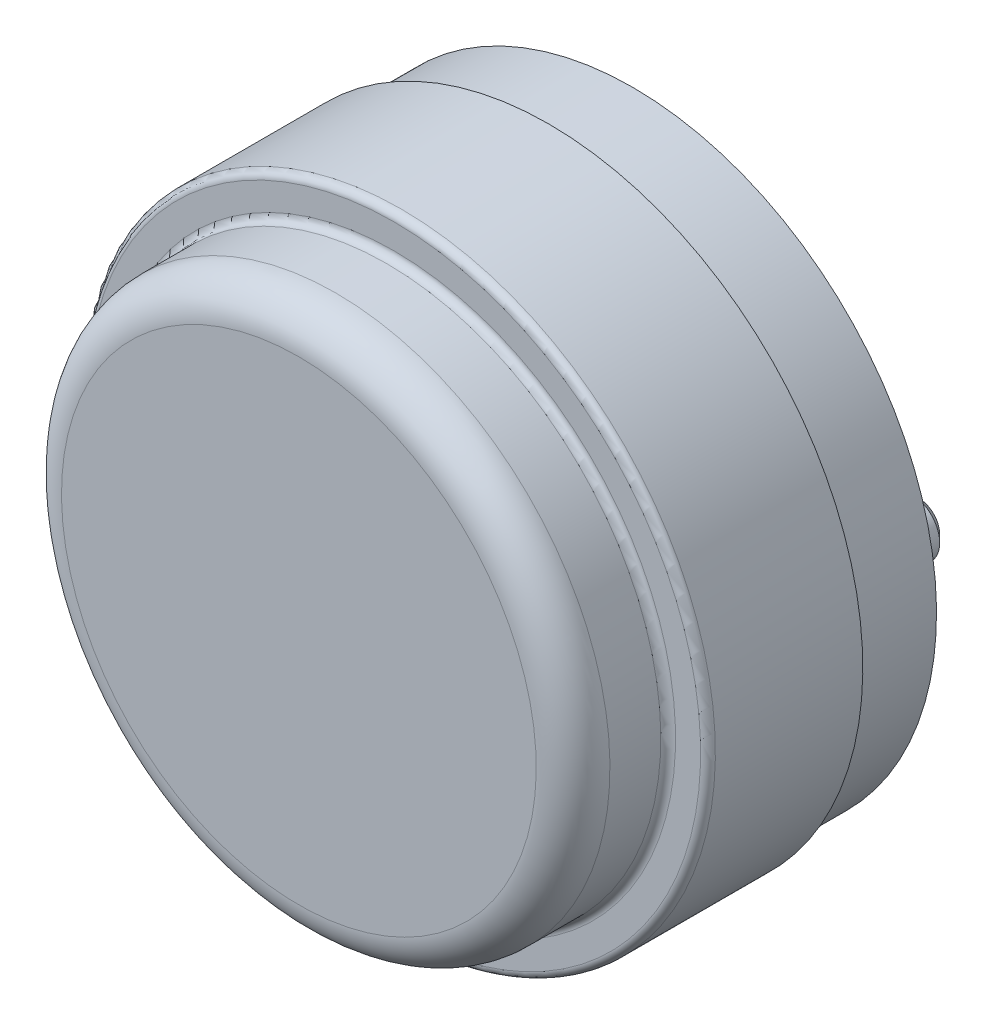
SolidWorks part; units mm, degrees
material "PP Copolymer"
ref_plane "Front" through (0, 0, 0) normal (0, 0, 1) x (1, 0, 0)
ref_plane "Top" through (0, 0, 0) normal (0, 1, 0) x (1, 0, 0)
ref_plane "Right" through (0, 0, 0) normal (1, 0, 0) x (0, 0, -1)
sketch "Sketch2" plane through (0, 0, 0) normal (1, 0, 0) x (0, 0, -1)
  line L0 (0, 0) -> (-7.62, 0) construction
  line L1 (-7.62, 0) -> (-11.5062, 0) construction
  line L2 (-7.62, 0) -> (-11.5062, 0)
  line L33 (-11.5062, 8.1788) -> (-11.5062, 0)
  line L34 (-8.4836, 9.4488) -> (-10.2362, 9.4488)
  line L35 (-8.2296, 10.5664) -> (-8.2296, 9.7028)
  line L36 (-2.8956, 10.8204) -> (-7.9756, 10.8204)
  line L37 (-2.8956, 10.4648) -> (-2.8956, 10.8204)
  line L38 (0, 10.4648) -> (-2.8956, 10.4648)
  line L39 (0, 5.08) -> (0, 10.4648)
  line L40 (-7.62, 5.08) -> (0, 5.08)
  line L41 (-7.62, 0) -> (-7.62, 5.08)
  arc A13 (-10.2362, 9.4488) -> (-11.5062, 8.1788) centre (-10.2362, 8.1788) ccw
  arc A14 (-8.4836, 9.4488) -> (-8.2296, 9.7028) centre (-8.4836, 9.7028) ccw
  arc A15 (-7.9756, 10.8204) -> (-8.2296, 10.5664) centre (-7.9756, 10.5664) ccw
  dimension "D4" = 1.27
  dimension "D5" = 0.254
  dimension "D7" = 0.254
  dimension "D1" = 7.62
  dimension "D2" = 8.1788
  dimension "D3" = 3.8862
  dimension "D6" = 3.2766
  dimension "D8" = 1.3716
  dimension "D9" = 5.08
  dimension "D10" = 0.3556
  dimension "D11" = 5.3848
  dimension "D12" = 2.8956
revolve "Revolve1" add sketch "Sketch2" angle 360 about L0
sketch "Sketch3" plane through (0, 0, 0) normal (0, 0, 1) x (1, 0, 0)
  line L0 (0, 0) -> (0, -12.1371) construction
  line L1 (7.4422, 0) -> (0, 0) construction
  circle A1 centre (7.4422, 0) radius 0.9716
  circle A2 centre (-7.4422, 0) radius 0.9716
  dimension "D1" = 1.9431
  dimension "D2" = 7.4422
extrude "Extrude2" add sketch "Sketch3" against normal blind 2.41
chamfer "Chamfer1" distance 0.25 angle 45 2 edges at (8.4138, 0, -2.41) (-8.4138, 0, -2.41)
